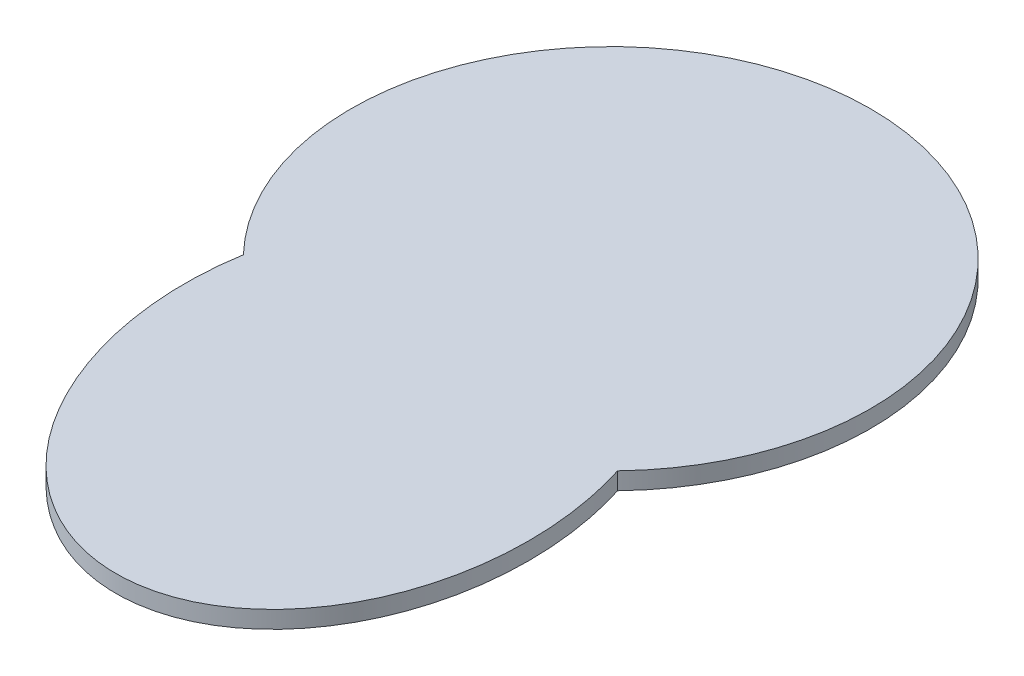
SolidWorks part; units mm, degrees
ref_plane "Front Plane" through (0, 0, 0) normal (0, 0, 1) x (1, 0, 0)
ref_plane "Top Plane" through (0, 0, 0) normal (0, 1, 0) x (1, 0, 0)
ref_plane "Right Plane" through (0, 0, 0) normal (1, 0, 0) x (0, 0, -1)
sketch "Sketch1" plane through (0, 0, 0) normal (0, 1, 0) x (1, 0, 0)
  line L0 (-44.6681, 18.3946) -> (41.9344, 18.3946) construction
  line L1 (-1.3669, -59.7593) -> (-1.3669, 120.2407) construction
  line L2 (-44.6681, 18.3946) -> (41.9344, 18.3946) construction
  line L3 (-1.3669, 120.2407) -> (-1.3669, -59.7593) construction
  line L4 (45.6863, 97.5476) -> (45.6863, 101.8305) construction
  line L6 (45.6863, -6.851) -> (45.6863, -4.9557) construction
  line L7 (45.6863, 101.8305) -> (41.9344, 101.8305) construction
  line L9 (-44.6681, -6.851) -> (-44.6681, 18.3946) construction
  arc A0 (41.9344, 18.3946) -> (-44.6681, 18.3946) centre (-1.3669, 60.1126) ccw
  ellipse E0 centre (0, 0) end of major axis (10.1519, -59.7758) minor radius 45.1879 (-44.6681, 18.3946) -> (41.9344, 18.3946) ccw
  dimension "D1" = 86.6025
  dimension "D2" = 180
extrude "Boss-Extrude1" add sketch "Sketch1" against normal blind 4
